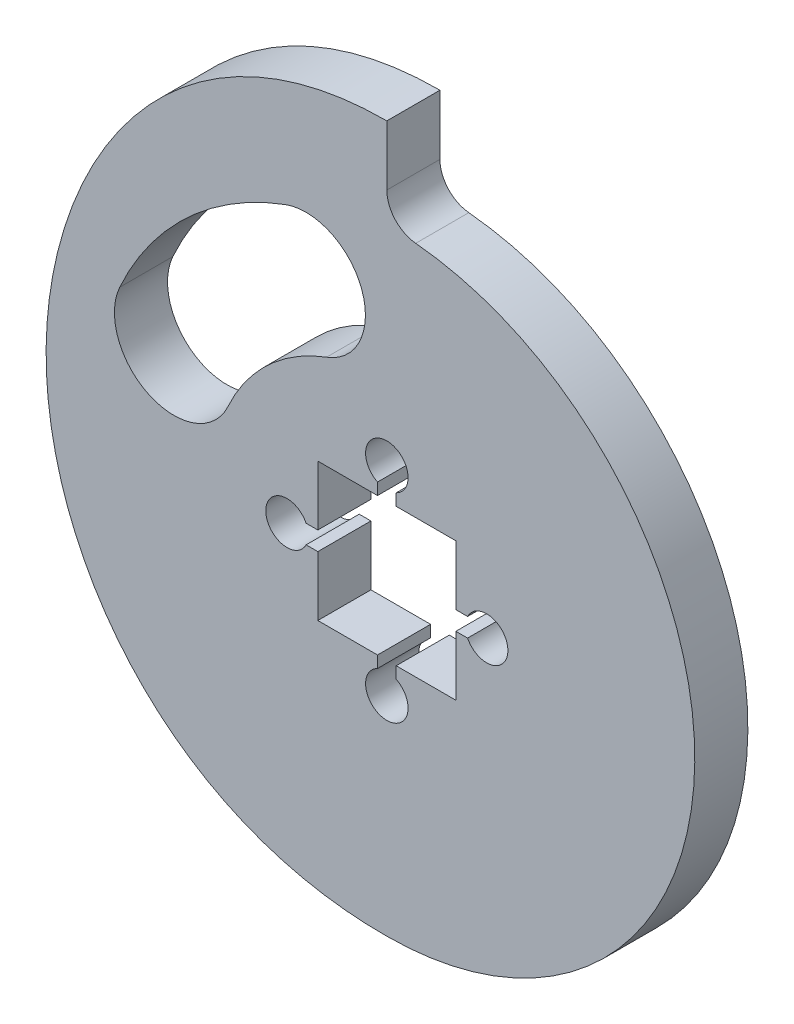
SolidWorks part; units mm, degrees
material "AISI 1020"
ref_plane "Front Plane" through (0, 0, 0) normal (0, 0, 1) x (1, 0, 0)
ref_plane "Top Plane" through (0, 0, 0) normal (0, 1, 0) x (1, 0, 0)
ref_plane "Right Plane" through (0, 0, 0) normal (1, 0, 0) x (0, 0, -1)
other "Center of Mass"
sketch "Sketch1" plane through (0, 0, 0) normal (0, 0, 1) x (1, 0, 0)
  line L0 (1.1176, -8.255) -> (8.255, -8.255)
  line L1 (-8.255, 8.255) -> (-1.1176, 8.255)
  line L2 (-8.255, 8.255) -> (-8.255, 1.1176)
  line L3 (-8.255, -8.255) -> (-1.1176, -8.255)
  line L4 (8.255, 8.255) -> (8.255, 1.1176)
  line L5 (8.255, -1.1176) -> (8.255, -8.255)
  line L6 (1.1176, 8.255) -> (8.255, 8.255)
  line L7 (8.255, 8.255) -> (-8.255, -8.255) construction
  line L9 (-9.6571, 1.1176) -> (-8.255, 1.1176)
  line L11 (-9.6571, -1.1176) -> (-8.255, -1.1176)
  line L14 (-1.1176, 9.6571) -> (-1.1176, 8.255)
  line L16 (1.1176, 9.6571) -> (1.1176, 8.255)
  line L25 (0, 0) -> (11.938, 0) construction
  line L27 (-8.255, -1.1176) -> (-8.255, -8.255)
  line L28 (0, 47.625) -> (0, 36.83)
  line L45 (-1.1176, -8.255) -> (-1.1176, -9.6571)
  line L47 (1.1176, -8.255) -> (1.1176, -9.6571)
  line L48 (8.255, -1.1176) -> (9.6571, -1.1176)
  line L50 (8.255, 1.1176) -> (9.6571, 1.1176)
  arc A2 (-1.1176, -9.6571) -> (1.1176, -9.6571) centre (0, -11.938) ccw
  arc A3 (9.6571, -1.1176) -> (9.6571, 1.1176) centre (11.938, 0) ccw
  arc A31 (-9.6571, 1.1176) -> (-9.6571, -1.1176) centre (-11.938, 0) ccw
  arc A32 (1.1176, 9.6571) -> (-1.1176, 9.6571) centre (0, 11.938) ccw
  arc A41 (0, -36.83) -> (0, 36.83) centre (0, 0) ccw
  spline S0 degree 3 poles (0, 47.625) (-26.6002, 47.625) (-56.1496, -0.4046) (-24.1552, -36.9841) (0, -36.83) knots 0 0 0 0 0.529165 1 1 1 1
  point P32 (-41.3837, 0)
  point P33 (0, 0)
  dimension "D2" = 11.938
  dimension "D4" = 5.08
  dimension "D6" = 16.51
  dimension "D7" = 40.64
  dimension "D14" = 73.66
  dimension "D3" = 47.625
  dimension "D1" = 16.51
  dimension "D5" = 2.2352
extrude "Boss-Extrude1" add sketch "Sketch1" along normal blind 6.35
sketch "Sketch5" plane through (0, 0, 6.35) normal (0, 0, 1) x (1, 0, 0)
  arc A0 (-25.4675, 11.4914) -> (-9.6739, 26.2118) centre (0, 0) cw construction
  arc A1 (-12.1364, 32.8839) -> (-31.9501, 14.4164) centre (0, 0) ccw
  arc A2 (-7.2115, 19.5397) -> (-18.9848, 8.5663) centre (0, 0) ccw
  arc A3 (-7.2115, 19.5397) -> (-12.1364, 32.8839) centre (-9.6739, 26.2118) ccw
  arc A4 (-31.9501, 14.4164) -> (-18.9848, 8.5663) centre (-25.4675, 11.4914) ccw
  point P4 (-19.05, 20.4387)
  point P9 (-6.8351, 24.4631)
  dimension "D1" = 27.94
  dimension "D2" = 7.112
  dimension "D3" = 21.59
  dimension "D4" = 19.05
extrude "Cut-Extrude1" cut sketch "Sketch5" against normal through all
fillet "Fillet2" radius 3.81 1 edges at (0, 36.83, 3.175)
